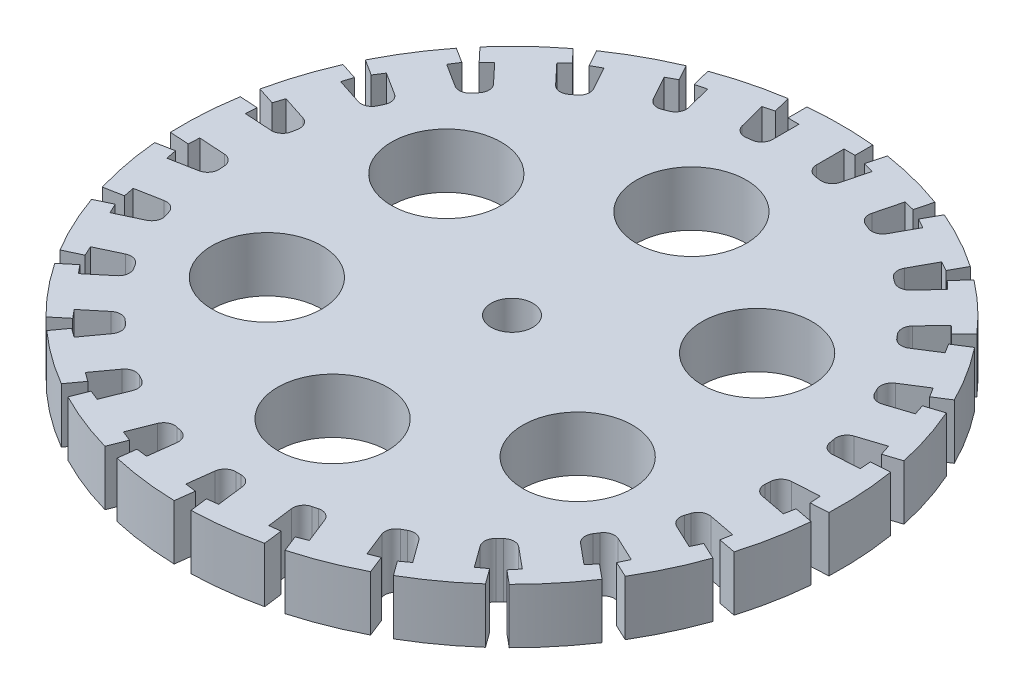
SolidWorks part; units mm, degrees
ref_plane "Front Plane" through (0, 0, 0) normal (0, 0, 1) x (1, 0, 0)
ref_plane "Top Plane" through (0, 0, 0) normal (0, 1, 0) x (1, 0, 0)
ref_plane "Right Plane" through (0, 0, 0) normal (1, 0, 0) x (0, 0, -1)
sketch "Sketch1" plane through (0, 0, 0) normal (0, 1, 0) x (1, 0, 0)
  line L0 (-2.54, 31.5285) -> (-2.54, 35.7186)
  line L1 (-2.54, 35.7186) -> (-3.81, 35.7186)
  line L2 (-3.81, 35.7186) -> (-3.81, 37.909)
  line L3 (2.54, 35.8476) -> (2.54, 31.5285)
  line L4 (2.54, 35.8476) -> (3.81, 35.8476)
  line L5 (3.81, 35.8476) -> (3.81, 37.909)
  line L6 (0, 31.6306) -> (0, 38.1) construction
  line L7 (5.3806, 31.1696) -> (6.4227, 35.2281)
  line L8 (6.4227, 35.2281) -> (5.1926, 35.544)
  line L9 (5.1926, 35.544) -> (5.7373, 37.6655)
  line L10 (11.3751, 34.0897) -> (10.301, 29.9063)
  line L11 (11.3751, 34.0897) -> (12.6052, 33.7739)
  line L12 (12.6052, 33.7739) -> (13.1179, 35.7705)
  line L13 (7.8662, 30.6369) -> (9.4751, 36.903) construction
  line L14 (12.9631, 28.8523) -> (14.9818, 32.5241)
  line L15 (14.9818, 32.5241) -> (13.8689, 33.136)
  line L16 (13.8689, 33.136) -> (14.9241, 35.0554)
  line L17 (19.4955, 30.1898) -> (17.4148, 26.4049)
  line L18 (19.4955, 30.1898) -> (20.6084, 29.578)
  line L19 (20.6084, 29.578) -> (21.6015, 31.3844)
  line L20 (15.2382, 27.7181) -> (18.3548, 33.3873) construction
  line L21 (19.7311, 24.722) -> (22.5995, 27.7765)
  line L22 (22.5995, 27.7765) -> (21.6737, 28.6459)
  line L23 (21.6737, 28.6459) -> (23.1731, 30.2426)
  line L24 (26.391, 24.393) -> (23.4343, 21.2445)
  line L25 (26.391, 24.393) -> (27.3167, 23.5237)
  line L26 (27.3167, 23.5237) -> (28.7279, 25.0264)
  line L27 (21.6526, 23.0577) -> (26.0812, 27.7737) construction
  line L28 (25.2594, 19.0384) -> (28.7972, 21.2836)
  line L29 (28.7972, 21.2836) -> (28.1167, 22.3559)
  line L30 (28.1167, 22.3559) -> (29.9661, 23.5296)
  line L31 (31.6281, 17.0635) -> (27.9814, 14.7492)
  line L32 (31.6281, 17.0635) -> (32.3086, 15.9912)
  line L33 (32.3086, 15.9912) -> (34.0491, 17.0958)
  line L34 (26.7066, 16.9485) -> (32.1689, 20.415) construction
  line L35 (29.2004, 12.1585) -> (33.1855, 13.4533)
  line L36 (33.1855, 13.4533) -> (32.7931, 14.6612)
  line L37 (32.7931, 14.6612) -> (34.8763, 15.3381)
  line L38 (34.878, 8.6618) -> (30.7703, 7.3271)
  line L39 (34.878, 8.6618) -> (35.2704, 7.454)
  line L40 (35.2704, 7.454) -> (37.231, 8.091)
  line L41 (30.0825, 9.7744) -> (36.2353, 11.7735) construction
  line L42 (31.3068, 4.5147) -> (35.4887, 4.7778)
  line L43 (35.4887, 4.7778) -> (35.4089, 6.0453)
  line L44 (35.4089, 6.0453) -> (37.595, 6.1828)
  line L45 (35.9364, -0.2841) -> (31.6257, -0.5553)
  line L46 (35.9364, -0.2841) -> (36.0161, -1.5516)
  line L47 (36.0161, -1.5516) -> (38.0734, -1.4222)
  line L48 (31.5682, 1.9861) -> (38.0248, 2.3923) construction
  line L49 (31.446, -3.4128) -> (35.5619, -4.198)
  line L50 (35.5619, -4.198) -> (35.7999, -2.9505)
  line L51 (35.7999, -2.9505) -> (37.9515, -3.3609)
  line L52 (34.7367, -9.2122) -> (30.4941, -8.4029)
  line L53 (34.7367, -9.2122) -> (34.4987, -10.4597)
  line L54 (34.4987, -10.4597) -> (36.5236, -10.846)
  line L55 (31.0703, -5.927) -> (37.4251, -7.1392) construction
  line L56 (29.6093, -11.1259) -> (33.4007, -12.91)
  line L57 (33.4007, -12.91) -> (33.9414, -11.7609)
  line L58 (33.9414, -11.7609) -> (35.9233, -12.6935)
  line L59 (31.3544, -17.5614) -> (27.4463, -15.7224)
  line L60 (31.3544, -17.5614) -> (30.8137, -18.7106)
  line L61 (30.8137, -18.7106) -> (32.6789, -19.5883)
  line L62 (28.6202, -13.4677) -> (34.4739, -16.2222) construction
  line L63 (25.9122, -18.1399) -> (29.1407, -20.8108)
  line L64 (29.1407, -20.8108) -> (29.9503, -19.8323)
  line L65 (29.9503, -19.8323) -> (31.638, -21.2285)
  line L66 (26.002, -24.8072) -> (22.674, -22.0541)
  line L67 (26.002, -24.8072) -> (25.1925, -25.7858)
  line L68 (25.1925, -25.7858) -> (26.7808, -27.0998)
  line L69 (24.3718, -20.1621) -> (29.3566, -24.2859) construction
  line L70 (20.5869, -24.0141) -> (23.0498, -27.404)
  line L71 (23.0498, -27.404) -> (24.0772, -26.6575)
  line L72 (24.0772, -26.6575) -> (25.3647, -28.4296)
  line L73 (19.0158, -30.4943) -> (16.4771, -27)
  line L74 (19.0158, -30.4943) -> (17.9883, -31.2408)
  line L75 (17.9883, -31.2408) -> (19.2, -32.9085)
  line L76 (18.592, -25.5897) -> (22.3946, -30.8235) construction
  line L77 (13.968, -28.3794) -> (15.5105, -32.2753)
  line L78 (15.5105, -32.2753) -> (16.6914, -31.8078)
  line L79 (16.6914, -31.8078) -> (17.4977, -33.8444)
  line L80 (10.8347, -34.2653) -> (9.2448, -30.2495)
  line L81 (10.8347, -34.2653) -> (9.6539, -34.7328)
  line L82 (9.6539, -34.7328) -> (10.4128, -36.6495)
  line L83 (11.644, -29.4094) -> (14.0255, -35.4245) construction
  line L84 (6.4715, -30.9615) -> (6.9967, -35.1186)
  line L85 (6.9967, -35.1186) -> (8.2567, -34.9595)
  line L86 (8.2567, -34.9595) -> (8.5312, -37.1326)
  line L87 (1.9729, -35.8833) -> (1.4316, -31.5982)
  line L88 (1.9729, -35.8833) -> (0.7129, -36.0424)
  line L89 (0.7129, -36.0424) -> (0.9713, -38.0876)
  line L90 (3.9644, -31.3812) -> (4.7752, -37.7996) construction
  line L91 (-1.4316, -31.5982) -> (-1.9568, -35.7553)
  line L92 (-1.9568, -35.7553) -> (-0.6968, -35.9145)
  line L93 (-0.6968, -35.9145) -> (-0.9713, -38.0876)
  line L94 (-7.0129, -35.2466) -> (-6.4715, -30.9615)
  line L95 (-7.0129, -35.2466) -> (-8.2729, -35.0874)
  line L96 (-8.2729, -35.0874) -> (-8.5312, -37.1326)
  line L97 (-3.9644, -31.3812) -> (-4.7752, -37.7996) construction
  line L98 (-9.2448, -30.2495) -> (-10.7873, -34.1454)
  line L99 (-10.7873, -34.1454) -> (-9.6065, -34.6129)
  line L100 (-9.6065, -34.6129) -> (-10.4128, -36.6495)
  line L101 (-15.558, -32.3952) -> (-13.968, -28.3794)
  line L102 (-15.558, -32.3952) -> (-16.7388, -31.9277)
  line L103 (-16.7388, -31.9277) -> (-17.4977, -33.8444)
  line L104 (-11.644, -29.4094) -> (-14.0255, -35.4245) construction
  line L105 (-16.4771, -27) -> (-18.94, -30.3899)
  line L106 (-18.94, -30.3899) -> (-17.9125, -31.1364)
  line L107 (-17.9125, -31.1364) -> (-19.2, -32.9085)
  line L108 (-23.1256, -27.5083) -> (-20.5869, -24.0141)
  line L109 (-23.1256, -27.5083) -> (-24.153, -26.7619)
  line L110 (-24.153, -26.7619) -> (-25.3647, -28.4296)
  line L111 (-18.592, -25.5897) -> (-22.3946, -30.8235) construction
  line L112 (-22.674, -22.0541) -> (-25.9026, -24.725)
  line L113 (-25.9026, -24.725) -> (-25.0931, -25.7036)
  line L114 (-25.0931, -25.7036) -> (-26.7808, -27.0998)
  line L115 (-29.2401, -20.893) -> (-25.9122, -18.1399)
  line L116 (-29.2401, -20.893) -> (-30.0496, -19.9145)
  line L117 (-30.0496, -19.9145) -> (-31.638, -21.2285)
  line L118 (-24.3718, -20.1621) -> (-29.3566, -24.2859) construction
  line L119 (-27.4463, -15.7224) -> (-31.2377, -17.5065)
  line L120 (-31.2377, -17.5065) -> (-30.697, -18.6556)
  line L121 (-30.697, -18.6556) -> (-32.6789, -19.5883)
  line L122 (-33.5174, -12.9649) -> (-29.6093, -11.1259)
  line L123 (-33.5174, -12.9649) -> (-34.0581, -11.8158)
  line L124 (-34.0581, -11.8158) -> (-35.9233, -12.6935)
  line L125 (-28.6202, -13.4677) -> (-34.4739, -16.2222) construction
  line L126 (-30.4941, -8.4029) -> (-34.61, -9.188)
  line L127 (-34.61, -9.188) -> (-34.372, -10.4355)
  line L128 (-34.372, -10.4355) -> (-36.5236, -10.846)
  line L129 (-35.6886, -4.2222) -> (-31.446, -3.4128)
  line L130 (-35.6886, -4.2222) -> (-35.9266, -2.9747)
  line L131 (-35.9266, -2.9747) -> (-37.9515, -3.3609)
  line L132 (-31.0703, -5.927) -> (-37.4251, -7.1392) construction
  line L133 (-31.6257, -0.5553) -> (-35.8076, -0.2922)
  line L134 (-35.8076, -0.2922) -> (-35.8874, -1.5597)
  line L135 (-35.8874, -1.5597) -> (-38.0734, -1.4222)
  line L136 (-35.6174, 4.7859) -> (-31.3068, 4.5147)
  line L137 (-35.6174, 4.7859) -> (-35.5376, 6.0534)
  line L138 (-35.5376, 6.0534) -> (-37.595, 6.1828)
  line L139 (-31.5682, 1.9861) -> (-38.0248, 2.3923) construction
  line L140 (-30.7703, 7.3271) -> (-34.7553, 8.622)
  line L141 (-34.7553, 8.622) -> (-35.1478, 7.4141)
  line L142 (-35.1478, 7.4141) -> (-37.231, 8.091)
  line L143 (-33.3082, 13.4932) -> (-29.2004, 12.1585)
  line L144 (-33.3082, 13.4932) -> (-32.9157, 14.701)
  line L145 (-32.9157, 14.701) -> (-34.8763, 15.3381)
  line L146 (-30.0825, 9.7744) -> (-36.2353, 11.7735) construction
  line L147 (-27.9814, 14.7492) -> (-31.5192, 16.9944)
  line L148 (-31.5192, 16.9944) -> (-32.1997, 15.9221)
  line L149 (-32.1997, 15.9221) -> (-34.0491, 17.0958)
  line L150 (-28.9061, 21.3527) -> (-25.2594, 19.0384)
  line L151 (-28.9061, 21.3527) -> (-28.2256, 22.425)
  line L152 (-28.2256, 22.425) -> (-29.9661, 23.5296)
  line L153 (-26.7066, 16.9485) -> (-32.1689, 20.415) construction
  line L154 (-23.4343, 21.2445) -> (-26.3027, 24.299)
  line L155 (-26.3027, 24.299) -> (-27.2285, 23.4296)
  line L156 (-27.2285, 23.4296) -> (-28.7279, 25.0264)
  line L157 (-22.6878, 27.8705) -> (-19.7311, 24.722)
  line L158 (-22.6878, 27.8705) -> (-21.762, 28.7399)
  line L159 (-21.762, 28.7399) -> (-23.1731, 30.2426)
  line L160 (-21.6526, 23.0577) -> (-26.0812, 27.7737) construction
  line L161 (-17.4148, 26.4049) -> (-19.4334, 30.0768)
  line L162 (-19.4334, 30.0768) -> (-20.5463, 29.465)
  line L163 (-20.5463, 29.465) -> (-21.6015, 31.3844)
  line L164 (-15.0439, 32.6371) -> (-12.9631, 28.8523)
  line L165 (-15.0439, 32.6371) -> (-13.931, 33.249)
  line L166 (-13.931, 33.249) -> (-14.9241, 35.0554)
  line L167 (-15.2382, 27.7181) -> (-18.3548, 33.3873) construction
  line L168 (-10.301, 29.9063) -> (-11.3431, 33.9648)
  line L169 (-11.3431, 33.9648) -> (-12.5732, 33.649)
  line L170 (-12.5732, 33.649) -> (-13.1179, 35.7705)
  line L171 (-6.4547, 35.3531) -> (-5.3806, 31.1696)
  line L172 (-6.4547, 35.3531) -> (-5.2246, 35.6689)
  line L173 (-5.2246, 35.6689) -> (-5.7373, 37.6655)
  line L174 (-7.8662, 30.6369) -> (-9.4751, 36.903) construction
  arc A0 (13.1179, 35.7705) -> (5.7373, 37.6655) centre (0, 0) ccw
  arc A1 (25.2594, 19.0384) -> (23.4343, 21.2445) centre (0, 0) ccw
  arc A2 (3.81, 37.909) -> (-3.81, 37.909) centre (0, 0) ccw
  arc A3 (-5.7373, 37.6655) -> (-13.1179, 35.7705) centre (0, 0) ccw
  arc A4 (-14.9241, 35.0554) -> (-21.6015, 31.3844) centre (0, 0) ccw
  arc A5 (21.6015, 31.3844) -> (14.9241, 35.0554) centre (0, 0) ccw
  arc A6 (28.7279, 25.0264) -> (23.1731, 30.2426) centre (0, 0) ccw
  arc A7 (34.0491, 17.0958) -> (29.9661, 23.5296) centre (0, 0) ccw
  arc A8 (19.7311, 24.722) -> (17.4148, 26.4049) centre (0, 0) ccw
  arc A9 (12.9631, 28.8523) -> (10.301, 29.9063) centre (0, 0) ccw
  arc A10 (5.3806, 31.1696) -> (2.54, 31.5285) centre (0, 0) ccw
  arc A11 (-2.54, 31.5285) -> (-5.3806, 31.1696) centre (0, 0) ccw
  arc A12 (-10.301, 29.9063) -> (-12.9631, 28.8523) centre (0, 0) ccw
  arc A13 (-17.4148, 26.4049) -> (-19.7311, 24.722) centre (0, 0) ccw
  arc A14 (29.2004, 12.1585) -> (27.9814, 14.7492) centre (0, 0) ccw
  arc A15 (37.231, 8.091) -> (34.8763, 15.3381) centre (0, 0) ccw
  arc A16 (31.3068, 4.5147) -> (30.7703, 7.3271) centre (0, 0) ccw
  arc A17 (38.0734, -1.4222) -> (37.595, 6.1828) centre (0, 0) ccw
  arc A18 (31.446, -3.4128) -> (31.6257, -0.5553) centre (0, 0) ccw
  arc A19 (36.5236, -10.846) -> (37.9515, -3.3609) centre (0, 0) ccw
  arc A20 (29.6093, -11.1259) -> (30.4941, -8.4029) centre (0, 0) ccw
  arc A21 (25.9122, -18.1399) -> (27.4463, -15.7224) centre (0, 0) ccw
  arc A22 (26.7808, -27.0998) -> (31.638, -21.2285) centre (0, 0) ccw
  arc A23 (20.5869, -24.0141) -> (22.674, -22.0541) centre (0, 0) ccw
  arc A24 (19.2, -32.9085) -> (25.3647, -28.4296) centre (0, 0) ccw
  arc A25 (13.968, -28.3794) -> (16.4771, -27) centre (0, 0) ccw
  arc A26 (10.4128, -36.6495) -> (17.4977, -33.8444) centre (0, 0) ccw
  arc A27 (6.4715, -30.9615) -> (9.2448, -30.2495) centre (0, 0) ccw
  arc A28 (0.9713, -38.0876) -> (8.5312, -37.1326) centre (0, 0) ccw
  arc A29 (-1.4316, -31.5982) -> (1.4316, -31.5982) centre (0, 0) ccw
  arc A30 (-8.5312, -37.1326) -> (-0.9713, -38.0876) centre (0, 0) ccw
  arc A31 (-9.2448, -30.2495) -> (-6.4715, -30.9615) centre (0, 0) ccw
  arc A32 (-17.4977, -33.8444) -> (-10.4128, -36.6495) centre (0, 0) ccw
  arc A33 (-16.4771, -27) -> (-13.968, -28.3794) centre (0, 0) ccw
  arc A34 (-25.3647, -28.4296) -> (-19.2, -32.9085) centre (0, 0) ccw
  arc A35 (-22.674, -22.0541) -> (-20.5869, -24.0141) centre (0, 0) ccw
  arc A36 (-35.9233, -12.6935) -> (-32.6789, -19.5883) centre (0, 0) ccw
  arc A37 (-31.638, -21.2285) -> (-26.7808, -27.0998) centre (0, 0) ccw
  arc A38 (-27.4463, -15.7224) -> (-25.9122, -18.1399) centre (0, 0) ccw
  arc A39 (-30.4941, -8.4029) -> (-29.6093, -11.1259) centre (0, 0) ccw
  arc A40 (-37.9515, -3.3609) -> (-36.5236, -10.846) centre (0, 0) ccw
  arc A41 (-31.6257, -0.5553) -> (-31.446, -3.4128) centre (0, 0) ccw
  arc A42 (-37.595, 6.1828) -> (-38.0734, -1.4222) centre (0, 0) ccw
  arc A43 (-30.7703, 7.3271) -> (-31.3068, 4.5147) centre (0, 0) ccw
  arc A44 (-34.8763, 15.3381) -> (-37.231, 8.091) centre (0, 0) ccw
  arc A45 (-27.9814, 14.7492) -> (-29.2004, 12.1585) centre (0, 0) ccw
  arc A46 (-29.9661, 23.5296) -> (-34.0491, 17.0958) centre (0, 0) ccw
  arc A47 (-23.4343, 21.2445) -> (-25.2594, 19.0384) centre (0, 0) ccw
  arc A48 (-23.1731, 30.2426) -> (-28.7279, 25.0264) centre (0, 0) ccw
  arc A49 (32.6789, -19.5883) -> (35.9233, -12.6935) centre (0, 0) ccw
  point P256 (0, 0)
  dimension "D1" = 76.2
  dimension "D2" = 2.54
  dimension "D3" = 2.54
  dimension "D4" = 1.27
  dimension "D5" = 1.27
  dimension "D6" = 25
extrude "Boss-Extrude2" add sketch "Sketch1" along normal blind 6.35 contours L0 L1 L2 A2 L5 L4 L3 A10 L7 L8 L9 A0 L12 L11 L10 A9 L14 L15 L16 A5 L19 L18 L17 A8 L21 L22 L23 A6 L26 L25 L24 A1 L28 L29 L30 A7 L33 L32 L31 A14 L35 L36 L37 A15 L40 L39 L38 A16 L42 L43 L44 A17 L47 L46 L45 A18 L49 L50 L51 A19 L54 L53 L52 A20 L56 L57 L58 A49 L61 L60 L59 A21 L63 L64 L65 A22 L68 L67 L66 A23 L70 L71 L72 A24 L75 L74 L73 A25 L77 L78 L79 A26 L82 L81 L80 A27 L84 L85 L86 A28 L89 L88 L87 A29 L91 L92 L93 A30 L96 L95 L94 A31 L98 L99 L100 A32 L103 L102 L101 A33 L105 L106 L107 A34 L110 L109 L108 A35 L112 L113 L114 A37 L117 L116 L115 A38 L119 L120 L121 A36 L124 L123 L122 A39 L126 L127 L128 A40 L131 L130 L129 A41 L133 L134 L135 A42 L138 L137 L136 A43 L140 L141 L142 A44 L145 L144 L143 A45 L147 L148 L149 A46 L152 L151 L150 A47 L154 L155 L156 A48 L159 L158 L157 A13 L161 L162 L163 A4 L166 L165 L164 A12 L168 L169 L170 A3 L173 L172 L171 A11
fillet "Fillet2" radius 1.27 47 edges at (17.4148, 3.175, -26.4049) (19.7311, 3.175, -24.722) (25.2594, 3.175, -19.0384) (29.2004, 3.175, -12.1585) (31.3068, 3.175, -4.5147) (31.446, 3.175, 3.4128) (29.6093, 3.175, 11.1259) (25.9122, 3.175, 18.1399) (22.674, 3.175, 22.0541) (16.4771, 3.175, 27) (9.2448, 3.175, 30.2495) (23.4343, 3.175, -21.2445) (27.9814, 3.175, -14.7492) (30.7703, 3.175, -7.3271) (31.6257, 3.175, 0.5553) (27.4463, 3.175, 15.7224) (30.4941, 3.175, 8.4029) (20.5869, 3.175, 24.0141) (13.968, 3.175, 28.3794) (6.4715, 3.175, 30.9615) (-1.4316, 3.175, 31.5982) (1.4316, 3.175, 31.5982) (-6.4715, 3.175, 30.9615) (-9.2448, 3.175, 30.2495) (-16.4771, 3.175, 27) (-22.674, 3.175, 22.0541) (-13.968, 3.175, 28.3794) (-20.5869, 3.175, 24.0141) (-25.9122, 3.175, 18.1399) (-27.4463, 3.175, 15.7224) (-30.4941, 3.175, 8.4029) (-31.6257, 3.175, 0.5553) (-30.7703, 3.175, -7.3271) (-27.9814, 3.175, -14.7492) (-23.4343, 3.175, -21.2445) (-17.4148, 3.175, -26.4049) (-10.301, 3.175, -29.9063) (-2.54, 3.175, -31.5285) (5.3806, 3.175, -31.1696) (12.9631, 3.175, -28.8523) (10.301, 3.175, -29.9063) (2.54, 3.175, -31.5285) (-5.3806, 3.175, -31.1696) (-12.9631, 3.175, -28.8523) (-19.7311, 3.175, -24.722) (-29.2004, 3.175, -12.1585) (-25.2594, 3.175, -19.0384)
fillet "Fillet3" radius 1.27 3 edges at (-31.3068, 3.175, -4.5147) (-31.446, 3.175, 3.4128) (-29.6093, 3.175, 11.1259)
sketch "Sketch2" plane through (0, 6.35, 0) normal (0, 1, 0) x (1, 0, 0)
  circle A0 centre (0, 0) radius 2.413
  circle A2 centre (0, 20.747) radius 6.35
  circle A3 centre (17.9675, 10.3735) radius 6.35
  circle A4 centre (17.9675, -10.3735) radius 6.35
  circle A5 centre (0, -20.747) radius 6.35
  circle A6 centre (-17.9675, -10.3735) radius 6.35
  circle A7 centre (-17.9675, 10.3735) radius 6.35
  point P3 (0, 20.747)
  point P17 (0, 0)
  dimension "D1" = 6
  dimension "D2" = 12.7
extrude "Cut-Extrude1" cut sketch "Sketch2" against normal up to next
